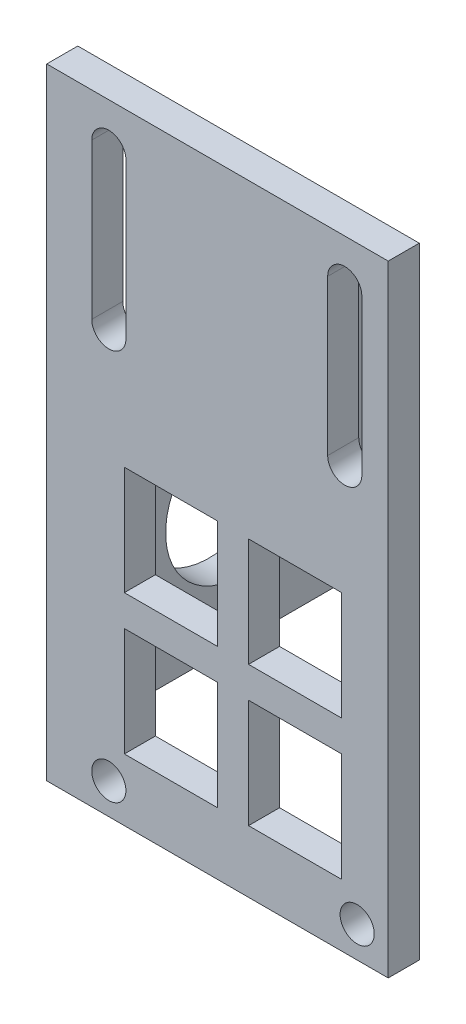
SolidWorks part; units mm, degrees
ref_plane "Front Plane" through (0, 0, 0) normal (0, 0, 1) x (1, 0, 0)
ref_plane "Top Plane" through (0, 0, 0) normal (0, 1, 0) x (1, 0, 0)
ref_plane "Right Plane" through (0, 0, 0) normal (1, 0, 0) x (0, 0, -1)
sketch "Sketch2" plane through (0, 0, 0) normal (1, 0, 0) x (0, 0, -1)
  line L1 (-21.15, 21.15) -> (21.15, 21.15)
  line L2 (-21.15, 21.15) -> (-21.15, -21.15)
  line L3 (-21.15, -21.15) -> (21.15, -21.15)
  line L4 (21.15, 21.15) -> (21.15, -21.15)
  line L5 (-21.15, 21.15) -> (21.15, -21.15) construction
  line L6 (-21.15, -21.15) -> (21.15, 21.15) construction
  circle A0 centre (-15.5, 15.5) radius 1.5
  circle A1 centre (15.5, 15.5) radius 1.5
  circle A2 centre (15.5, -15.5) radius 1.5
  circle A3 centre (-15.5, -15.5) radius 1.5
  circle A4 centre (0, 0) radius 12
  point P0 (0, 0)
  dimension "D7" = 3
  dimension "D8" = 24
  dimension "D1" = 42.3
  dimension "D2" = 42.3
  dimension "D3" = 15.5
  dimension "D4" = 31
  dimension "D5" = 31
  dimension "D6" = 31
extrude "Boss-Extrude1" add sketch "Sketch2" along normal blind 5
sketch "Sketch3" plane through (0, 0, 21.15) normal (0, 0, 1) x (1, 0, 0)
  line L0 (0, 21.15) -> (0, -21.15) construction
  line L1 (0, 70) -> (55, 70)
  line L2 (0, 70) -> (0, -30)
  line L3 (0, -30) -> (55, -30)
  line L4 (55, 70) -> (55, -30)
  line L5 (48, 63) -> (48, 38) construction
  line L6 (12.5, 20) -> (27.5, 20)
  line L7 (12.5, 20) -> (12.5, 2.5)
  line L8 (12.5, 2.5) -> (27.5, 2.5)
  line L9 (27.5, 20) -> (27.5, 2.5)
  line L10 (32.5, 20) -> (47.5, 20)
  line L11 (32.5, 20) -> (32.5, 2.5)
  line L12 (32.5, 2.5) -> (47.5, 2.5)
  line L13 (47.5, 20) -> (47.5, 2.5)
  line L14 (32.5, -2.5) -> (47.5, -2.5)
  line L15 (32.5, -2.5) -> (32.5, -20)
  line L16 (32.5, -20) -> (47.5, -20)
  line L17 (47.5, -2.5) -> (47.5, -20)
  line L18 (12.5, -2.5) -> (27.5, -2.5)
  line L19 (12.5, -2.5) -> (12.5, -20)
  line L20 (12.5, -20) -> (27.5, -20)
  line L21 (27.5, -2.5) -> (27.5, -20)
  line L22 (50.75, 63) -> (50.75, 38)
  line L23 (45.25, 63) -> (45.25, 38)
  line L24 (10, 63) -> (10, 38) construction
  line L25 (12.75, 63) -> (12.75, 38)
  line L26 (7.25, 63) -> (7.25, 38)
  circle A1 centre (50, -25) radius 2.75
  circle A3 centre (10, -25) radius 2.75
  arc A4 (50.75, 63) -> (45.25, 63) centre (48, 63) ccw
  arc A5 (45.25, 38) -> (50.75, 38) centre (48, 38) ccw
  arc A6 (12.75, 63) -> (7.25, 63) centre (10, 63) ccw
  arc A7 (7.25, 38) -> (12.75, 38) centre (10, 38) ccw
  point P21 (48, 50.5)
  point P37 (10, 50.5)
  dimension "D9" = 2.75
  dimension "D10" = 10
  dimension "D19" = 2.75
  dimension "D1" = 55
  dimension "D3" = 70
  dimension "D4" = 12.5
  dimension "D5" = 50
  dimension "D6" = 50
  dimension "D7" = 2.5
  dimension "D8" = 10
  dimension "D11" = 7
  dimension "D12" = 7
  dimension "D13" = 7
  dimension "D14" = 5
  dimension "D15" = 5
  dimension "D16" = 5
  dimension "D17" = 10
  dimension "D18" = 12.5
  dimension "D20" = 10
  dimension "D21" = 15
  dimension "D22" = 100
  dimension "D23" = 17.5
  dimension "D24" = 17.5
  dimension "D25" = 15
  dimension "D26" = 15
  dimension "D27" = 17.5
  dimension "D28" = 17.5
  dimension "D29" = 15
  dimension "D30" = 25
  dimension "D31" = 25
extrude "Boss-Extrude2" add sketch "Sketch3" along normal blind 5
fillet "Fillet1" radius 5 2 edges at (2.5, -21.15, 21.15) (2.5, 21.15, 21.15)
